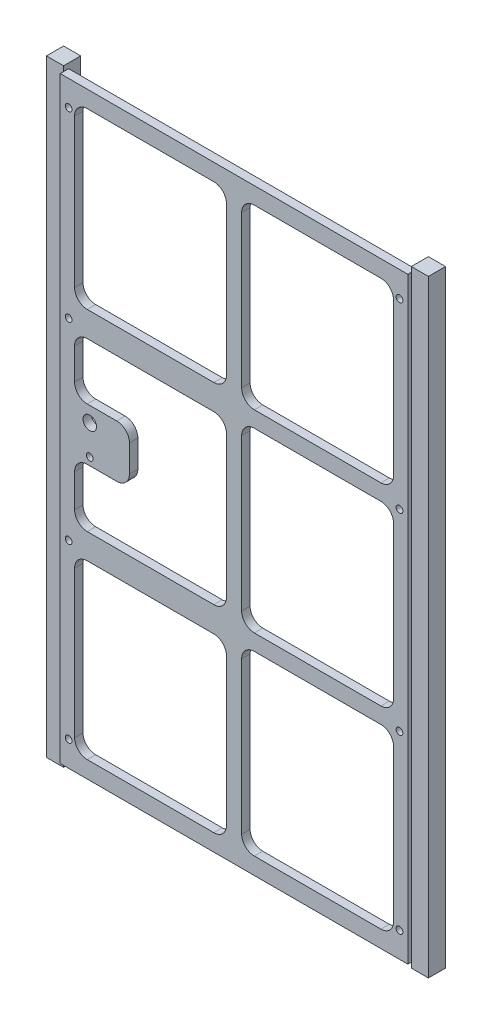
SolidWorks part; units mm, degrees
ref_plane "Přední rovina" through (0, 0, 0) normal (0, 0, 1) x (1, 0, 0)
ref_plane "Horní rovina" through (0, 0, 0) normal (0, 1, 0) x (1, 0, 0)
ref_plane "Pravá rovina" through (0, 0, 0) normal (1, 0, 0) x (0, 0, -1)
sketch "Skica1" plane through (0, 0, 0) normal (0, 0, 1) x (1, 0, 0)
  line L0 (0, 0) -> (0, 177) construction
  line L1 (113.15, -180) -> (113.15, 180)
  line L6 (113.15, 180) -> (103, 180)
  line L7 (103, 180) -> (103, 177)
  line L8 (103, 177) -> (-103, 177)
  line L9 (0, 0) -> (113.15, 0) construction
  line L10 (-103, 180) -> (-103, 177)
  line L11 (-113.15, 180) -> (-103, 180)
  line L12 (-113.15, -180) -> (-113.15, 180)
  line L13 (103, -180) -> (103, -177)
  line L14 (113.15, -180) -> (103, -180)
  line L15 (103, -177) -> (-103, -177)
  line L16 (-103, -180) -> (-103, -177)
  line L17 (-113.15, -180) -> (-103, -180)
  point P17 (-113.15, 0)
  dimension "D1" = 10.15
  dimension "D2" = 360
  dimension "D3" = 226.3
  dimension "D4" = 3
extrude "Přidat vysunutím1" add sketch "Skica1" along normal offset from surface (5 mm away) 5 up to plane "Přední rovina"
sketch "Skica5" plane through (0, 0, 0) normal (0, 0, -1) x (-1, 0, 0)
  line L0 (103, 180) -> (113.15, 180)
  line L10 (113.15, 180) -> (113.15, -180)
  line L11 (113.15, -180) -> (103, -180)
  line L12 (103, -180) -> (103, 180)
  line L13 (0, 0) -> (0, 177) construction
  line L14 (-103, 177) -> (103, 177) construction
  line L15 (-113.15, -180) -> (-103, -180)
  line L16 (-103, 180) -> (-113.15, 180)
  line L17 (-113.15, 180) -> (-113.15, -180)
  line L18 (-103, -180) -> (-103, 180)
extrude "Přidat vysunutím5" add sketch "Skica5" along normal offset from surface (7.15 mm away) 7.15 up to face at (0, 0, 0) offset beyond the face yes
sketch "Skica7" plane through (0, 0, 5) normal (0, 0, 1) x (1, 0, 0)
  line L0 (103, 177) -> (-103, 177) construction
  line L1 (0, 0) -> (0, 177) construction
  line L6 (12, 62) -> (12, 159.5) construction
  line L7 (12, 159.5) -> (4.5, 159.5) construction
  line L8 (12, 159.5) -> (12, 167) construction
  line L9 (12, 167) -> (87, 167)
  line L10 (49.5, 167) -> (49.5, 114.5) construction
  line L11 (4.5, 159.5) -> (4.5, 69.5)
  line L12 (49.5, 114.5) -> (4.5, 114.5) construction
  line L13 (94.5, 159.5) -> (94.5, 69.5)
  line L14 (12, 62) -> (87, 62)
  line L15 (-12, 167) -> (-87, 167)
  line L16 (-4.5, 159.5) -> (-4.5, 69.5)
  line L17 (-12, 62) -> (-87, 62)
  line L18 (-94.5, 159.5) -> (-94.5, 69.5)
  line L35 (94.5, 45) -> (94.5, -45)
  line L36 (12, -52.5) -> (87, -52.5)
  line L37 (4.5, 45) -> (4.5, -45)
  line L38 (12, 52.5) -> (87, 52.5)
  line L39 (-94.5, 45) -> (-94.5, -45)
  line L40 (-12, -52.5) -> (-87, -52.5)
  line L41 (-4.5, 45) -> (-4.5, -45)
  line L42 (-12, 52.5) -> (-87, 52.5)
  line L43 (94.5, -69.5) -> (94.5, -159.5)
  line L44 (12, -167) -> (87, -167)
  line L45 (4.5, -69.5) -> (4.5, -159.5)
  line L46 (12, -62) -> (87, -62)
  line L47 (-94.5, -69.5) -> (-94.5, -159.5)
  line L48 (-12, -167) -> (-87, -167)
  line L49 (-4.5, -69.5) -> (-4.5, -159.5)
  line L50 (-12, -62) -> (-87, -62)
  arc A0 (12, 167) -> (4.5, 159.5) centre (12, 159.5) ccw
  arc A1 (87, 167) -> (94.5, 159.5) centre (87, 159.5) cw
  arc A2 (87, 62) -> (94.5, 69.5) centre (87, 69.5) ccw
  arc A3 (12, 62) -> (4.5, 69.5) centre (12, 69.5) cw
  arc A4 (-87, 167) -> (-94.5, 159.5) centre (-87, 159.5) ccw
  arc A5 (-12, 167) -> (-4.5, 159.5) centre (-12, 159.5) cw
  arc A6 (-12, 62) -> (-4.5, 69.5) centre (-12, 69.5) ccw
  arc A7 (-87, 62) -> (-94.5, 69.5) centre (-87, 69.5) cw
  arc A8 (87, -52.5) -> (94.5, -45) centre (87, -45) ccw
  arc A9 (12, -52.5) -> (4.5, -45) centre (12, -45) cw
  arc A10 (12, 52.5) -> (4.5, 45) centre (12, 45) ccw
  arc A11 (87, 52.5) -> (94.5, 45) centre (87, 45) cw
  arc A12 (-87, 52.5) -> (-94.5, 45) centre (-87, 45) ccw
  arc A13 (-87, -52.5) -> (-94.5, -45) centre (-87, -45) cw
  arc A14 (-12, -52.5) -> (-4.5, -45) centre (-12, -45) ccw
  arc A15 (-12, 52.5) -> (-4.5, 45) centre (-12, 45) cw
  arc A16 (87, -167) -> (94.5, -159.5) centre (87, -159.5) ccw
  arc A17 (12, -167) -> (4.5, -159.5) centre (12, -159.5) cw
  arc A18 (12, -62) -> (4.5, -69.5) centre (12, -69.5) ccw
  arc A19 (87, -62) -> (94.5, -69.5) centre (87, -69.5) cw
  arc A20 (-87, -62) -> (-94.5, -69.5) centre (-87, -69.5) ccw
  arc A21 (-87, -167) -> (-94.5, -159.5) centre (-87, -159.5) cw
  arc A22 (-12, -167) -> (-4.5, -159.5) centre (-12, -159.5) ccw
  arc A23 (-12, -62) -> (-4.5, -69.5) centre (-12, -69.5) cw
  point P18 (94.5, 114.5)
  dimension "D5" = 15
  dimension "D6" = 3
  dimension "D1" = 90
  dimension "D2" = 105
  dimension "D3" = 4.5
  dimension "D4" = 10
  dimension "D7" = 114.5
extrude "Odebrat vysunutím1" cut sketch "Skica7" against normal through all both and the other way through all
sketch "Skica9" plane through (0, 0, -7.15) normal (0, 0, -1) x (-1, 0, 0)
  line L0 (0, 0) -> (98, 0) construction
  line L2 (98, 0) -> (98, 162) construction
  circle A0 centre (98, 162) radius 2
  circle A1 centre (98, 54) radius 2
  circle A3 centre (98, -162) radius 2
  circle A4 centre (98, -54) radius 2 [skipped]
  circle A5 centre (98, -60) radius 2
  dimension "D2" = 4
  dimension "D5" = 4
  dimension "D6" = 108
  dimension "D7" = 2
  dimension "D8" = 114
  dimension "D1" = 162
  dimension "D3" = 162
  dimension "D4" = 98
extrude "Odebrat vysunutím3" cut sketch "Skica9" against normal through all
mirror "Zrcadlit2" about plane through (0, 0, 0) normal (1, 0, 0) of "Odebrat vysunutím3"
sketch "Skica13" plane through (0, 0, -7.15) normal (0, 0, -1) x (-1, 0, 0)
  circle A0 centre (98, 162) radius 3.5
  circle A1 centre (98, 54) radius 3.5
  circle A3 centre (98, -162) radius 3.5
  circle A4 centre (98, -54) radius 3.5 [skipped]
  circle A5 centre (98, -60) radius 3.5
  dimension "D1" = 4
  dimension "D3" = 7
  dimension "D2" = 108
  dimension "D4" = 2
  dimension "D5" = 114
extrude "Odebrat vysunutím9" cut sketch "Skica13" against normal blind 9.15
mirror "Zrcadlit3" about plane through (0, 0, 0) normal (1, 0, 0) of "Odebrat vysunutím9"
sketch "Skica14" plane through (0, 0, 0) normal (0, 0, -1) x (-1, 0, 0)
  line L0 (0, 0) -> (0, 56.5) construction
  line L1 (94.5, 71.5) -> (94.5, 41.5)
  line L2 (12, 49) -> (87, 49)
  line L4 (0, 56.5) -> (0, 71.5) construction
  line L5 (0, 71.5) -> (12, 71.5) construction
  line L6 (0, 56.5) -> (49.5, 56.5) construction
  line L8 (49.5, 56.5) -> (49.5, 64) construction
  line L14 (12, 64) -> (87, 64)
  line L15 (4.5, 71.5) -> (4.5, 41.5)
  arc A4 (4.5, 71.5) -> (12, 64) centre (12, 71.5) ccw
  arc A5 (94.5, 71.5) -> (87, 64) centre (87, 71.5) cw
  arc A6 (94.5, 41.5) -> (87, 49) centre (87, 41.5) ccw
  arc A7 (4.5, 41.5) -> (12, 49) centre (12, 41.5) cw
  point P13 (-6.6967, 39.3033)
  point P15 (-49.5, 64)
  point P17 (-94.5, 54)
  point P18 (94.5, 56.5)
  point P20 (49.5, 64)
  point P22 (-4.5, 54)
  point P25 (4.5, 56.5)
  dimension "D3" = 49.5
  dimension "D5" = 15
  dimension "D1" = 56.5
  dimension "D2" = 12
  dimension "D4" = 15
extrude "Přidat vysunutím6" add sketch "Skica14" against normal blind 5 contours L2 A6 L1 A5 L14 A4 L15 A7
sketch "Skica15" plane through (0, 0, 0) normal (0, 0, -1) x (-1, 0, 0)
  line L0 (0, 0) -> (94.5, 0) construction
  line L1 (94.5, -45) -> (94.5, 41.5) construction
  line L2 (94.5, 0) -> (94.5, 15.5) construction
  line L3 (94.5, 15.5) -> (94.5, 23) construction
  line L4 (94.5, 23) -> (87, 23) construction
  line L5 (87, 15.5) -> (69.5, 15.5)
  line L6 (69.5, 15.5) -> (69.5, 8) construction
  line L7 (62, 8) -> (62, -8)
  line L8 (94.5, 23) -> (94.5, -23)
  line L9 (87, -15.5) -> (69.5, -15.5)
  line L10 (85.5, 6.5) -> (85.5, 15.5) construction
  arc A0 (87, 15.5) -> (94.5, 23) centre (87, 23) ccw
  arc A1 (69.5, 15.5) -> (62, 8) centre (69.5, 8) ccw
  arc A2 (69.5, -15.5) -> (62, -8) centre (69.5, -8) cw
  arc A3 (87, -15.5) -> (94.5, -23) centre (87, -23) cw
  circle A4 centre (85.5, 6.5) radius 4
  point P11 (62, 0)
  dimension "D7" = 8
  dimension "D1" = 31
  dimension "D2" = 7.5
  dimension "D3" = 7.5
  dimension "D4" = 25
  dimension "D5" = 7.5
  dimension "D6" = 9
  dimension "D8" = 16
extrude "Přidat vysunutím7" add sketch "Skica15" against normal blind 5
sketch "Skica16" plane through (0, 0, 0) normal (0, 0, -1) x (-1, 0, 0)
  line L0 (62, 0) -> (85.5, 0) construction
  line L2 (62, 8) -> (62, -8) construction
  line L3 (85.5, 0) -> (85.5, -11) construction
  line L4 (69.5, -15.5) -> (87, -15.5) construction
  circle A0 centre (85.5, -11) radius 2
  dimension "D3" = 4
  dimension "D1" = 23.5
  dimension "D2" = 4.5
extrude "Odebrat vysunutím10" cut sketch "Skica16" against normal through all
sketch "Skica17" plane through (0, 0, 0) normal (0, 0, -1) x (-1, 0, 0)
  circle A0 centre (85.5, -11) radius 3.5
  dimension "D1" = 7
extrude "Odebrat vysunutím11" cut sketch "Skica17" against normal blind 2
pattern_linear "LinPole1" count 2 spacing 114 along (0, -1, 0) of "Přidat vysunutím6"
sketch "Skica18" plane through (0, 180, 0) normal (0, 1, 0) x (1, 0, 0)
  line L0 (-103, -5) -> (-103, 7.15) construction
  line L1 (-113.15, -5) -> (-103, -5)
  line L2 (-113.15, -5) -> (-113.15, -3)
  line L3 (-113.15, -3) -> (-103, -3)
  line L4 (-103, -5) -> (-103, -3)
  line L5 (0, 0) -> (0, 40.2894) construction
  line L6 (103, 0) -> (-103, 0) construction
  line L7 (113.15, -3) -> (103, -3)
  line L8 (103, -5) -> (103, -3)
  line L9 (113.15, -5) -> (103, -5)
  line L10 (113.15, -5) -> (113.15, -3)
  dimension "D1" = 2
extrude "Odebrat vysunutím12" cut sketch "Skica18" against normal through all both and the other way through all
